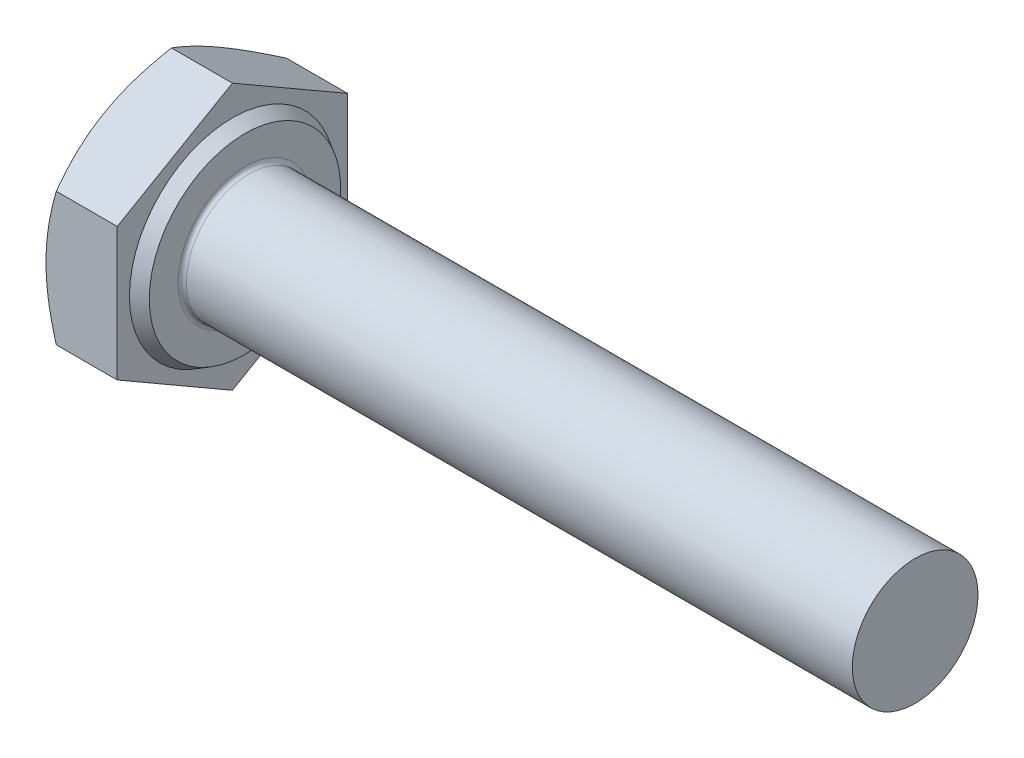
SolidWorks part; units mm, degrees
ref_plane "前视" through (0, 0, 0) normal (0, 0, 1) x (1, 0, 0)
ref_plane "上视" through (0, 0, 0) normal (0, 1, 0) x (1, 0, 0)
ref_plane "右视" through (0, 0, 0) normal (1, 0, 0) x (0, 0, -1)
sketch "草图1" plane through (0, 0, 0) normal (1, 0, 0) x (0, 0, -1)
  line L0 (2.75, 1.5877) -> (2.75, -1.5877)
  line L1 (-2.75, 1.5877) -> (-2.75, -1.5877)
  line L2 (2.75, -1.5877) -> (0, -3.1754)
  line L3 (0, -3.1754) -> (-2.75, -1.5877)
  line L4 (2.75, 1.5877) -> (0, 3.1754)
  line L5 (0, 3.1754) -> (-2.75, 1.5877)
  circle A0 centre (0, 0) radius 3.005 construction
  dimension "e" = 6.01
  dimension "s" = 5.5
  dimension "D2" = 120
  dimension "D3" = 2.75
  dimension "D4" = 2.75
  dimension "D5" = 2.75
extrude "基体-拉伸" add sketch "草图1" along normal blind 2
sketch "草图2" plane through (0, 0, 0) normal (0, 0, 1) x (1, 0, 0)
  line L0 (0, 1.5877) -> (0, -1.5877) construction
  line L1 (0, 0) -> (27, 0)
  line L2 (0, 0) -> (0, 1.5)
  line L3 (0, 1.5) -> (27, 1.5)
  line L4 (27, 0) -> (27, 1.067)
  line L5 (2, 3.1754) -> (2, 1.5877) construction
  line L6 (0, 0) -> (-3.6, 0) construction
  line L7 (0, 0) -> (13.5, 0) construction
  line L8 (27, -1.067) -> (90.335, -1.5) construction
  line L9 (0, -1.5) -> (90.335, -1.5) construction
  line L10 (2.5, 1.5) -> (2.5, 0) construction
  line L11 (2, 13.0554) -> (2, -1.27) construction
  line L12 (2, 1.5877) -> (2, -1.5877) construction
  line L14 (27, 1.5) -> (27, 1.067)
  dimension "l" = 25
  dimension "d" = 3
  dimension "Minor_dia" = 2.134
  dimension "p" = 0.5
  dimension "b" = 25
  dimension "da" = 3.6
revolve "凸台-旋转1" add sketch "草图2" angle 360 about L7
cosmetic thread "螺旋线1" parameters "Thread_length"=24.5, "Thread_minor"=2.134
sketch "草图3" plane through (0, 0, 0) normal (0, 0, 1) x (1, 0, 0)
  line L0 (0, 2.75) -> (3.1324, 8.1754)
  line L1 (0, 3.1754) -> (0, 1.5877) construction
  line L2 (3.1324, 8.1754) -> (3.1324, 13.1754)
  line L3 (3.1324, 13.1754) -> (-10, 13.1754)
  line L4 (-10, 13.1754) -> (-10, 2.75)
  line L5 (-10, 2.75) -> (0, 2.75)
  line L6 (0, 0) -> (99.06, 0) construction
  line L7 (2, 3.1754) -> (0, 3.1754) construction
  dimension "D1" = 2.75
  dimension "D2" = 5
  dimension "D3" = 10
  dimension "D4" = 5
  dimension "Head_ch_ang" = 30
revolve "切除-旋转1" cut sketch "草图3" angle 360 about L6
sketch "草图4" plane through (0, 0, 0) normal (0, 0, 1) x (1, 0, 0)
  line L0 (0, 0) -> (248.9073, 0) construction
  line L2 (2, 0) -> (2, 2.285) construction
  line L3 (2, -1.5) -> (2, 1.5) construction
  line L4 (2, 3.1754) -> (2, 1.5877) construction
  line L9 (2, 2.285) -> (1.7, 2.4582)
  line L10 (1.7, 2.4582) -> (1.7, 3.1754)
  line L11 (2, 3.1754) -> (0.2456, 3.1754) construction
  line L12 (1.7, 3.1754) -> (2, 3.1754)
  line L13 (2, 3.1754) -> (2, 2.285)
  dimension "D1" = 120
  dimension "c" = 0.3
  dimension "dw" = 4.57
revolve "切除-旋转3" cut sketch "草图4" angle 360 about L0
fillet "圆角" radius 0.1 1 edges at (2, 0, -1.5)
sketch "草图6" plane through (0, 0, 0) normal (0, 0, 1) x (1, 0, 0)
  line L0 (0, 0) -> (27, 0) construction
  line L1 (27, -1.5) -> (27, 1.5) construction
  line L2 (27, 0) -> (27, 1.5) construction
  line L4 (26.75, 1.5) -> (27.25, 1.5)
  line L5 (26.75, 1.5) -> (27, 1.067)
  line L6 (27, 1.067) -> (27.25, 1.5)
  dimension "D1" = 0.5
revolve "切除-旋转4" cut sketch "草图6" angle 360 about L0
pattern_linear "阵列(线性)1" [suppressed]
sketch "草图7" plane through (27, 0, 0) normal (1, 0, 0) x (0, 0, -1)
  circle A0 centre (0, 0) radius 3.3487
extrude "切除-拉伸1" cut sketch "草图7" against normal blind 9
